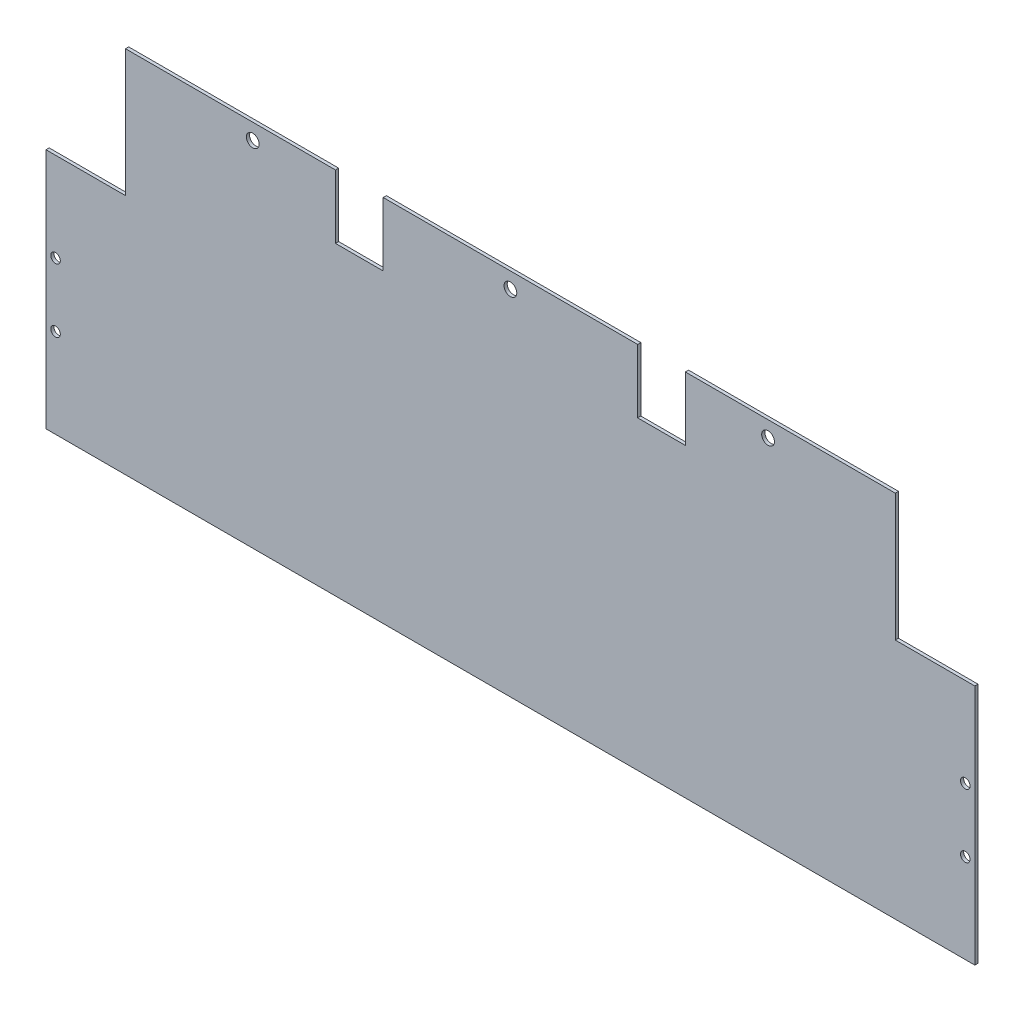
SolidWorks part; units mm, degrees
material "Thornel Mat VMA"
ref_plane "前视基准面" through (0, 0, 0) normal (0, 0, 1) x (1, 0, 0)
ref_plane "上视基准面" through (0, 0, 0) normal (0, 1, 0) x (1, 0, 0)
ref_plane "右视基准面" through (0, 0, 0) normal (1, 0, 0) x (0, 0, -1)
sketch "草图1" plane through (0, 0, 0) normal (0, 0, 1) x (1, 0, 0)
  line L0 (0, 0) -> (0, 76)
  line L1 (0, 76) -> (25, 76)
  line L2 (25, 76) -> (25, 116)
  line L3 (25, 116) -> (267, 116)
  line L4 (267, 116) -> (267, 76)
  line L5 (267, 76) -> (292, 76)
  line L6 (292, 76) -> (292, 0)
  line L7 (292, 0) -> (0, 0)
  line L8 (3, 48) -> (3, 28) construction
  line L9 (0, 38) -> (292, 38) construction
  line L10 (146, 116) -> (146, 0) construction
  line L11 (289, 48) -> (289, 28) construction
  circle A0 centre (3, 48) radius 1.5
  circle A1 centre (3, 28) radius 1.5
  circle A2 centre (289, 28) radius 1.5
  circle A3 centre (289, 48) radius 1.5
  point P13 (3, 38)
  dimension "D7" = 3
  dimension "D1" = 292
  dimension "D2" = 76
  dimension "D3" = 40
  dimension "D4" = 25
  dimension "D5" = 20
  dimension "D6" = 3
extrude "凸台-拉伸1" add sketch "草图1" along normal blind 1
sketch "草图2" plane through (0, 0, 1) normal (0, 0, 1) x (1, 0, 0)
  line L0 (146, 116) -> (146, 0) construction
  line L1 (267, 116) -> (25, 116) construction
  line L2 (0, 0) -> (292, 0) construction
  line L3 (186, 116) -> (186, 96)
  line L4 (91, 116) -> (106, 116)
  line L5 (91, 116) -> (91, 96)
  line L6 (91, 96) -> (106, 96)
  line L7 (106, 116) -> (106, 96)
  line L8 (201, 96) -> (186, 96)
  line L9 (201, 116) -> (201, 96)
  line L10 (201, 116) -> (186, 116)
  line L11 (25, 116) -> (25, 76) construction
  circle A0 centre (65, 111) radius 2
  circle A1 centre (227, 111) radius 2
  circle A2 centre (146, 111) radius 2
  point P14 (98.5, 116)
  point P15 (193.5, 116)
  dimension "D4" = 4
  dimension "D7" = 4
  dimension "D1" = 95
  dimension "D2" = 15
  dimension "D3" = 20
  dimension "D5" = 5
  dimension "D6" = 40
extrude "切除-拉伸1" cut sketch "草图2" against normal through all
